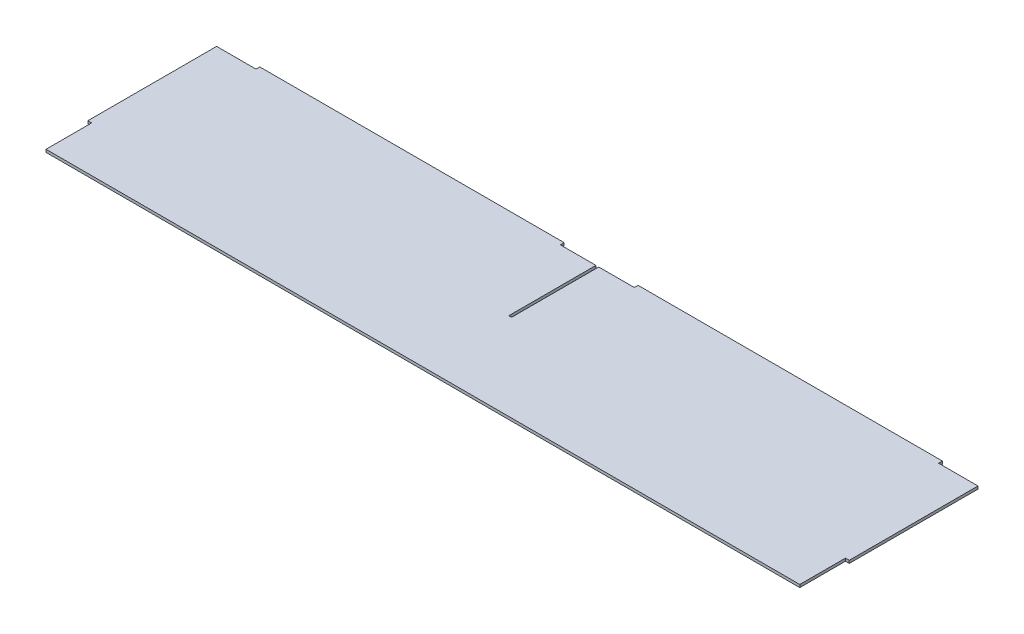
SolidWorks part; units mm, degrees
material "6061-T6 (SS)"
ref_plane "X-Y Datum" through (0, 0, 0) normal (0, 0, 1) x (1, 0, 0)
ref_plane "X-Z Datum" through (0, 0, 0) normal (0, 1, 0) x (1, 0, 0)
ref_plane "Y-Z Datum" through (0, 0, 0) normal (1, 0, 0) x (0, 0, -1)
sketch "Sketch1" plane through (0, 0, 0) normal (0, 1, 0) x (1, 0, 0)
  line L1 (-317.6778, 72.771) -> (317.6778, 72.771)
  line L2 (-317.6778, 72.771) -> (-317.6778, -72.771)
  line L3 (-317.6778, -72.771) -> (317.6778, -72.771)
  line L4 (317.6778, 72.771) -> (317.6778, -72.771)
  line L5 (-317.6778, 72.771) -> (317.6778, -72.771) construction
  line L6 (-317.6778, -72.771) -> (317.6778, 72.771) construction
  point P0 (0, 0)
  dimension "D1" = 635.3556
  dimension "D2" = 145.542
extrude "Boss-Extrude1" add sketch "Sketch1" along normal mid plane 2.286
sketch "Sketch2" plane through (0, 0, -72.771) normal (0, 0, -1) x (-1, 0, 0)
  line L0 (-317.6778, 1.143) -> (317.6778, 1.143) construction
  line L20 (-317.6778, -1.143) -> (317.6778, -1.143) construction
  line L21 (-284.8269, -1.143) -> (-30.8265, -1.143)
  line L22 (30.8189, -1.143) -> (284.8193, -1.143)
  line L40 (30.8189, -1.143) -> (30.8229, 1.143)
  line L41 (30.8229, 1.143) -> (284.8233, 1.143)
  line L42 (284.8233, 1.143) -> (284.8193, -1.143)
  line L56 (-284.8269, -1.143) -> (-284.8229, 1.143)
  line L57 (-284.8229, 1.143) -> (-30.8225, 1.143)
  line L58 (-30.8225, 1.143) -> (-30.8265, -1.143)
extrude "Boss-Extrude2" add sketch "Sketch2" along normal blind 3.175
sketch "Sketch3" plane through (0, -1.143, 0) normal (0, -1, 0) x (1, 0, 0)
  line L0 (-314.3758, 72.898) -> (-314.3758, 34.544)
  line L1 (-317.6778, 72.771) -> (-314.5028, 72.771)
  line L2 (-317.6778, 72.771) -> (-317.6778, 34.671)
  line L3 (-317.6778, 34.671) -> (-314.5028, 34.671)
  line L4 (-314.5028, 72.771) -> (-314.5028, 34.671)
  line L5 (-317.8048, 34.544) -> (-314.3758, 34.544)
  line L6 (-317.8048, 72.898) -> (-317.8048, 34.544)
  line L7 (-317.8048, 72.898) -> (-314.3758, 72.898)
  line M6 (317.6778, 72.771) -> (-317.6778, 72.771)
  line M7 (-317.6778, 72.771) -> (-317.6778, -72.771)
  dimension "D1" = 3.175
  dimension "D2" = 38.1
  dimension "D3" = 0.127
extrude "Cut-Extrude1" cut sketch "Sketch3" against normal through all contours L4 L3 M6 M7
mirror "Mirror1" about plane through (0, 0, 0) normal (1, 0, 0) of "Cut-Extrude1"
sketch "Sketch4" plane through (0, -1.143, 0) normal (0, -1, 0) x (1, 0, 0)
  line L0 (30.8265, -72.771) -> (-30.8189, -72.771) construction
  line L1 (-1.143, -72.771) -> (1.1938, -72.771)
  line L2 (-1.143, -72.771) -> (-1.143, 0)
  line L3 (-1.143, 0) -> (1.1938, 0)
  line L4 (1.1938, -72.771) -> (1.1938, 0)
  line L5 (-1.143, -72.771) -> (-1.143, 34.671) construction
  line L6 (1.3589, -72.9361) -> (1.3589, 0.1651)
  line L7 (-1.3081, 0.1651) -> (1.3589, 0.1651)
  line L8 (-1.3081, -72.9361) -> (-1.3081, 0.1651)
  line L9 (-1.3081, -72.9361) -> (1.3589, -72.9361)
  line M15 (-30.8189, -72.771) -> (30.8265, -72.771)
  dimension "D1" = 2.3368
  dimension "D2" = 72.771
  dimension "D3" = 0.1651
extrude "Cut-Extrude2" cut sketch "Sketch4" against normal through all contours L4 L3 L2 M15
